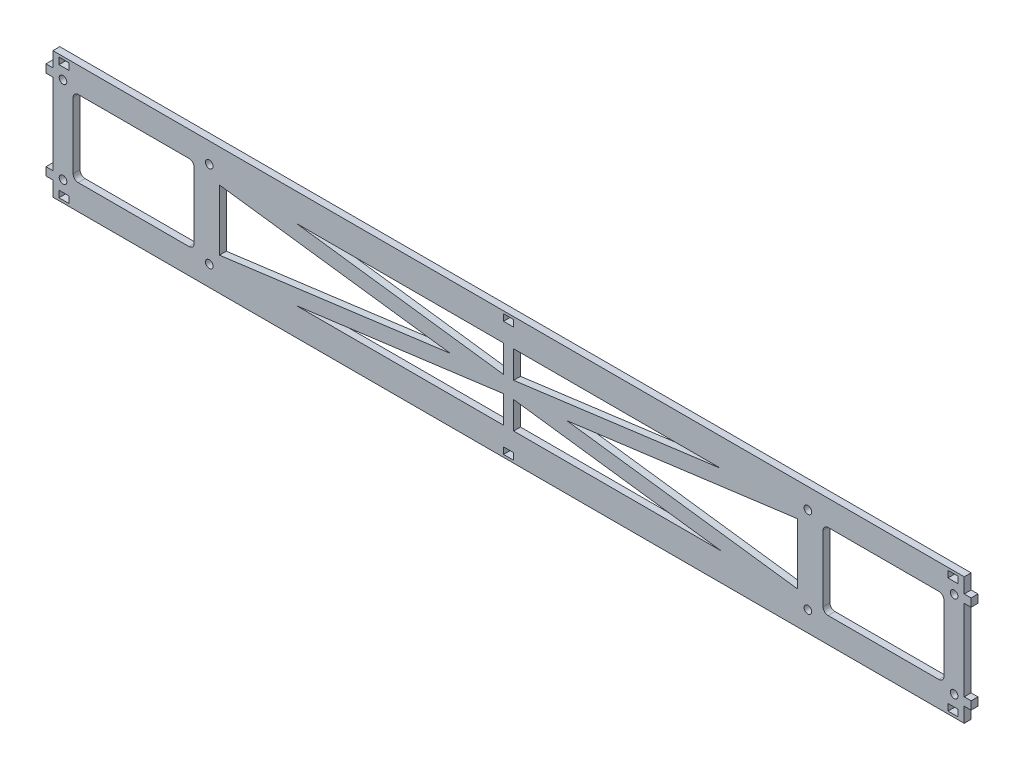
SolidWorks part; units mm, degrees
material "Delrin 2700 NC010, Low Viscosity Acetal Copolymer (SS)"
ref_plane "Front Plane" through (0, 0, 0) normal (0, 0, 1) x (1, 0, 0)
ref_plane "Top Plane" through (0, 0, 0) normal (0, 1, 0) x (1, 0, 0)
ref_plane "Right Plane" through (0, 0, 0) normal (1, 0, 0) x (0, 0, -1)
ref_plane "Horiz centerline" through (0, 0, 0) normal (0, 1, 0) x (-1, 0, 0)
ref_plane "Vertical plane" through (0, 0, 0) normal (1, 0, 0) x (0, 0, -1)
sketch "Sketch1" plane through (0, 0, 0) normal (0, 0, 1) x (1, 0, 0)
  line L0 (0, 13.3795) -> (0, -13.3795) construction
  line L1 (-114.3, 13.3795) -> (114.3, 13.3795) construction
  line L2 (-114.3, 13.3795) -> (-114.3, -13.3795)
  line L3 (-114.3, -13.3795) -> (114.3, -13.3795) construction
  line L4 (114.3, 13.3795) -> (114.3, -13.3795)
  line L5 (-114.3, 0) -> (114.3, 0) construction
  line L6 (-107.95, -9.5694) -> (-80.16, -9.5694)
  line L7 (-1.27, -8.9344) -> (-1.27, -2.0887)
  line L8 (78.89, -8.2995) -> (78.89, 8.2995)
  line L9 (-109.22, -8.2995) -> (-109.22, 8.2995)
  line L10 (-107.95, 9.5694) -> (-80.16, 9.5694)
  line L11 (-78.89, -8.2995) -> (-78.89, 8.2995)
  line L12 (107.95, 9.5694) -> (80.16, 9.5694)
  line L13 (109.22, -8.2995) -> (109.22, 8.2995)
  line L14 (107.95, -9.5694) -> (80.16, -9.5694)
  line L15 (0, 0) -> (-75.08, 9.887) construction
  line L16 (-14.5912, 0) -> (-72.54, 7.631)
  line L17 (-53.2557, -8.9345) -> (-1.27, -8.9344)
  line L18 (-72.54, -7.631) -> (-72.54, 7.631)
  line L19 (-1.27, 8.9345) -> (-1.27, 2.0887)
  line L20 (-1.27, -2.0887) -> (-53.2557, -8.9345)
  line L21 (-0.2487, -1.8887) -> (-75.3287, 7.9983) construction
  line L22 (-53.2557, 8.9345) -> (-1.27, 8.9345)
  line L23 (-1.27, 2.0887) -> (-53.2557, 8.9345)
  line L24 (0, 0) -> (-75.08, -9.887) construction
  line L25 (-14.5912, 0) -> (-72.54, -7.631)
  line L26 (1.27, -8.9344) -> (1.27, -2.0887)
  line L27 (1.27, 8.9345) -> (1.27, 2.0887)
  line L28 (1.27, -2.0887) -> (53.2557, -8.9345)
  line L29 (53.2557, -8.9345) -> (1.27, -8.9344)
  line L30 (0, 0) -> (75.08, -9.887) construction
  line L31 (14.5912, 0) -> (72.54, -7.631)
  line L32 (72.54, -7.631) -> (72.54, 7.631)
  line L33 (14.5912, 0) -> (72.54, 7.631)
  line L34 (0, 0) -> (75.08, 9.887) construction
  line L35 (53.2557, 8.9345) -> (1.27, 8.9345)
  line L36 (1.27, 2.0887) -> (53.2557, 8.9345)
  line L37 (-114.3, 15.9195) -> (114.3, 15.9195)
  line L38 (110.236, 15.2845) -> (110.236, 13.6335)
  line L39 (-114.3, -15.9195) -> (114.3, -15.9195)
  line L40 (-116.84, -15.9195) -> (116.84, -15.9195) construction
  line L41 (-114.3, 13.3795) -> (-114.3, 15.9195)
  line L42 (-114.3, -13.3795) -> (-114.3, -15.9195)
  line L43 (-116.84, 15.9195) -> (116.84, 15.9195) construction
  line L44 (-116.84, 15.9195) -> (-116.84, -15.9195) construction
  line L45 (114.3, -13.3795) -> (114.3, -15.9195)
  line L46 (114.3, 13.3795) -> (114.3, 15.9195)
  line L47 (116.84, 15.9195) -> (116.84, -15.9195) construction
  line L48 (112.776, -15.2845) -> (110.236, -15.2845)
  line L49 (112.776, -15.2845) -> (112.776, -13.6335)
  line L50 (112.776, -13.6335) -> (110.236, -13.6335)
  line L51 (110.236, -15.2845) -> (110.236, -13.6335)
  line L52 (112.776, 13.6335) -> (110.236, 13.6335)
  line L53 (112.776, 15.2845) -> (112.776, 13.6335)
  line L54 (112.776, 15.2845) -> (110.236, 15.2845)
  line L55 (-112.776, 15.2845) -> (-110.236, 15.2845)
  line L56 (-112.776, 15.2845) -> (-112.776, 13.6335)
  line L57 (-112.776, 13.6335) -> (-110.236, 13.6335)
  line L58 (-110.236, 15.2845) -> (-110.236, 13.6335)
  line L59 (-110.236, -15.2845) -> (-110.236, -13.6335)
  line L60 (-112.776, -13.6335) -> (-110.236, -13.6335)
  line L61 (-112.776, -15.2845) -> (-112.776, -13.6335)
  line L62 (-112.776, -15.2845) -> (-110.236, -15.2845)
  line L63 (-1.27, -15.2844) -> (-1.27, -13.6334)
  line L64 (1.27, -15.2844) -> (1.27, -13.6334)
  line L65 (1.27, -15.2844) -> (-1.27, -15.2844)
  line L66 (1.27, -13.6334) -> (-1.27, -13.6334)
  line L67 (0, -13.3795) -> (0, -15.9194) construction
  line L70 (1.27, 15.2844) -> (1.27, 13.6334)
  line L71 (-1.27, 15.2844) -> (-1.27, 13.6334)
  line L72 (1.27, 13.6334) -> (-1.27, 13.6334)
  line L73 (1.27, 15.2844) -> (-1.27, 15.2844)
  circle A0 centre (-111.76, 10.8395) radius 0.9525
  circle A1 centre (-111.76, -10.8395) radius 0.9525
  circle A2 centre (-75.08, 10.8395) radius 0.9525
  circle A3 centre (-75.08, -10.8395) radius 0.9525
  circle A4 centre (75.08, 10.8395) radius 0.9525
  circle A5 centre (111.76, 10.8395) radius 0.9525
  circle A6 centre (111.76, -10.8395) radius 0.9525
  circle A7 centre (75.08, -10.8395) radius 0.9525
  arc A8 (-107.95, 9.5694) -> (-109.22, 8.2995) centre (-107.95, 8.2995) ccw
  arc A9 (-78.89, 8.2995) -> (-80.16, 9.5694) centre (-80.16, 8.2995) ccw
  arc A10 (-78.89, -8.2995) -> (-80.16, -9.5694) centre (-80.16, -8.2995) cw
  arc A11 (-107.95, -9.5694) -> (-109.22, -8.2995) centre (-107.95, -8.2995) cw
  arc A12 (107.95, -9.5694) -> (109.22, -8.2995) centre (107.95, -8.2995) ccw
  arc A13 (78.89, -8.2995) -> (80.16, -9.5694) centre (80.16, -8.2995) ccw
  arc A14 (78.89, 8.2995) -> (80.16, 9.5694) centre (80.16, 8.2995) cw
  arc A15 (107.95, 9.5694) -> (109.22, 8.2995) centre (107.95, 8.2995) cw
  point P12 (-109.22, 0)
  point P40 (-78.89, 0)
  point P53 (78.89, 0)
  point P54 (109.22, 0)
  point P69 (-72.54, 0)
  point P107 (0, -13.6334)
  point P113 (0, 13.6334)
  dimension "D4" = 1.905
  dimension "D7" = 36.68
  dimension "D9" = 1.905
  dimension "D13" = 1.27
  dimension "D1" = 228.6
  dimension "D2" = 26.7589
  dimension "D5" = 2.54
  dimension "D6" = 2.54
  dimension "D8" = 2.54
  dimension "D10" = 5.08
  dimension "D11" = 3.81
  dimension "D12" = 1.27
  dimension "D15" = 4.445
  dimension "D16" = 2.54
  dimension "D17" = 1.27
  dimension "D18" = 1.905
  dimension "D14" = 1.27
  dimension "D19" = 1.905
  dimension "D20" = 2.54
  dimension "D21" = 2.54
  dimension "D3" = 3.81
  dimension "D22" = 1.651
  dimension "D23" = 1.524
  dimension "D24" = 0.635
  dimension "D25" = 2.54
  dimension "D26" = 1.651
extrude "Boss-Extrude1" add sketch "Sketch1" along normal blind 1.7272
sketch "Sketch2" plane through (0, 0, 1.7272) normal (0, 0, 1) x (1, 0, 0)
  line L0 (114.3, 15.9195) -> (-114.3, 15.9195) construction
  line L1 (-105.41, 15.9195) -> (-5.08, 15.9194)
  line L2 (-105.41, 15.9195) -> (-105.41, 13.3795)
  line L3 (-105.41, 13.3795) -> (-5.08, 13.3794)
  line L4 (-5.08, 15.9194) -> (-5.08, 13.3794)
  line L5 (-114.3, 15.9195) -> (-114.3, -15.9195) construction
  line L6 (-1.27, 13.6334) -> (1.27, 13.6334) construction
  line L7 (-96.52, 0) -> (24.3212, 0) construction
  line L9 (0, 0) -> (0, 22.425) construction
  line L10 (-5.08, -15.9194) -> (-5.08, -13.3794)
  line L11 (-105.41, -13.3795) -> (-5.08, -13.3794)
  line L12 (-105.41, -15.9195) -> (-105.41, -13.3795)
  line L13 (-105.41, -15.9195) -> (-5.08, -15.9194)
  line L14 (0, 0) -> (0, -22.425) construction
  line L15 (96.52, 0) -> (-24.3212, 0) construction
  line L16 (105.41, -15.9195) -> (5.08, -15.9194)
  line L17 (105.41, -15.9195) -> (105.41, -13.3795)
  line L18 (105.41, -13.3795) -> (5.08, -13.3794)
  line L19 (5.08, -15.9194) -> (5.08, -13.3794)
  line L20 (5.08, 15.9194) -> (5.08, 13.3794)
  line L21 (105.41, 13.3795) -> (5.08, 13.3794)
  line L22 (105.41, 15.9195) -> (105.41, 13.3795)
  line L23 (105.41, 15.9195) -> (5.08, 15.9194)
  point P8 (0, 13.6334)
  dimension "D1" = 2.54
  dimension "D2" = 8.89
  dimension "D3" = 5.08
extrude "Cut-Extrude1" [suppressed] cut sketch "Sketch2" against normal blind 1.7272
sketch "Sketch3" plane through (0, 0, 0) normal (0, 0, 1) x (1, 0, 0)
  line L0 (-114.3, 15.9195) -> (-114.3, -15.9195) construction
  line L1 (-114.3, 12.192) -> (-116.0272, 12.192)
  line L2 (-114.3, 12.192) -> (-114.3, 10.16)
  line L3 (-114.3, 10.16) -> (-116.0272, 10.16)
  line L4 (-116.0272, 12.192) -> (-116.0272, 10.16)
  line L5 (-114.3, 15.9195) -> (-114.3, -15.9195) construction
  line L6 (0, 0) -> (-35.971, 0) construction
  line L7 (-116.0272, -12.192) -> (-116.0272, -10.16)
  line L8 (-114.3, -10.16) -> (-116.0272, -10.16)
  line L9 (-114.3, -12.192) -> (-114.3, -10.16)
  line L10 (-114.3, -12.192) -> (-116.0272, -12.192)
  line L11 (114.3, -12.192) -> (116.0272, -12.192)
  line L12 (0, 0) -> (0, 20.5798) construction
  line L13 (114.3, -12.192) -> (114.3, -10.16)
  line L14 (114.3, -10.16) -> (116.0272, -10.16)
  line L15 (116.0272, -12.192) -> (116.0272, -10.16)
  line L16 (116.0272, 12.192) -> (116.0272, 10.16)
  line L17 (114.3, 10.16) -> (116.0272, 10.16)
  line L18 (114.3, 12.192) -> (114.3, 10.16)
  line L19 (114.3, 12.192) -> (116.0272, 12.192)
  point P6 (-114.3, 0)
  dimension "D1" = 1.7272
  dimension "D2" = 2.032
  dimension "D3" = 10.16
extrude "Boss-Extrude2" add sketch "Sketch3" along normal up to surface (1.7272 mm away) up to face at (0, -14.4589, 1.7272)
